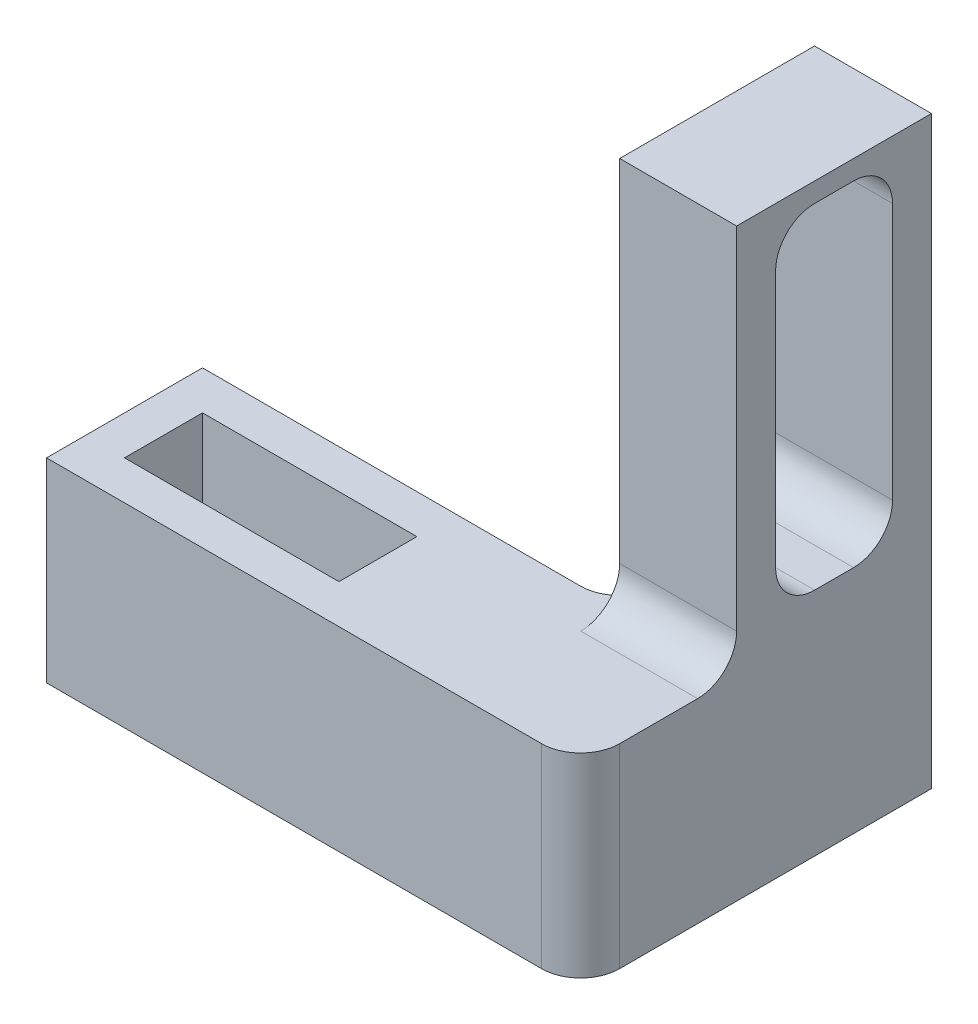
SolidWorks part; units mm, degrees
ref_plane "Front Plane" through (0, 0, 0) normal (0, 0, 1) x (1, 0, 0)
ref_plane "Top Plane" through (0, 0, 0) normal (0, 1, 0) x (1, 0, 0)
ref_plane "Right Plane" through (0, 0, 0) normal (1, 0, 0) x (0, 0, -1)
sketch "Sketch1" plane through (0, 0, 0) normal (0, 1, 0) x (1, 0, 0)
  line L1 (-2.5135, 3.907) -> (2.9865, 3.907)
  line L2 (-2.5135, 3.907) -> (-2.5135, 1.907)
  line L3 (-2.5135, 1.907) -> (2.9865, 1.907)
  line L4 (2.9865, 3.907) -> (2.9865, 1.907)
  line L5 (-3.5135, 4.907) -> (3.9865, 4.907)
  line L6 (-3.5135, 4.907) -> (-3.5135, 0.907)
  line L7 (-3.5135, 0.907) -> (3.9865, 0.907)
  line L8 (3.9865, 4.907) -> (3.9865, 0.907)
  dimension "D1" = 2
  dimension "D2" = 5.5
  dimension "D3" = 1
  dimension "D4" = 1
  dimension "D5" = 1
  dimension "D6" = 1
extrude "Boss-Extrude1" add sketch "Sketch1" along normal blind 5
sketch "Sketch2" plane through (0, 0, -4.907) normal (0, 0, -1) x (-1, 0, 0)
  line L1 (-3.9865, 5) -> (-10.1865, 5)
  line L2 (-3.9865, 5) -> (-3.9865, 0)
  line L3 (-3.9865, 0) -> (-10.1865, 0)
  line L4 (-10.1865, 5) -> (-10.1865, 0)
  circle A0 centre (-0.2365, 2.5) radius 6.5 construction
  dimension "D1" = 13
  dimension "D2" = 6.2
extrude "Boss-Extrude2" add sketch "Sketch2" against normal blind 4
sketch "Sketch3" plane through (0, 0, -4.907) normal (0, 0, -1) x (-1, 0, 0)
  line L0 (-10.1865, 0) -> (3.5135, 0) construction
  line L1 (-10.1865, 5) -> (-7.1865, 5)
  line L2 (-10.1865, 5) -> (-10.1865, 0)
  line L3 (-10.1865, 0) -> (-7.1865, 0)
  line L4 (-7.1865, 5) -> (-7.1865, 0)
  dimension "D1" = 3
extrude "Boss-Extrude3" add sketch "Sketch3" along normal blind 5
sketch "Sketch4" plane through (0, 5, 0) normal (0, 1, 0) x (1, 0, 0)
  line L0 (10.1865, 0.907) -> (10.1865, 9.907) construction
  line L1 (7.1865, 9.907) -> (10.1865, 9.907)
  line L2 (7.1865, 9.907) -> (7.1865, 4.9094)
  line L3 (7.1865, 4.9094) -> (10.1865, 4.9094)
  line L4 (10.1865, 9.907) -> (10.1865, 4.9094)
extrude "Boss-Extrude4" add sketch "Sketch4" along normal blind 10
sketch "Sketch5" plane through (10.1865, 0, 0) normal (1, 0, 0) x (0, 0, -1)
  line L0 (4.9094, 15) -> (4.9094, 5) construction
  line L1 (5.9094, 14.5) -> (8.9094, 14.5)
  line L2 (5.9094, 14.5) -> (5.9094, 5.9101)
  line L3 (5.9094, 5.9101) -> (8.9094, 5.9101)
  line L4 (8.9094, 14.5) -> (8.9094, 5.9101)
  line L5 (4.9094, 15) -> (9.907, 15) construction
  dimension "D1" = 1
  dimension "D2" = 3
  dimension "D3" = 0.5
extrude "Cut-Extrude1" cut sketch "Sketch5" against normal blind 10
fillet "Fillet1" radius 1 1 edges
fillet "Fillet2" radius 1 1 edges at (10.1865, 2.5, -0.907)
fillet "Fillet3" radius 1 1 edges
sketch "Sketch6" plane through (0, 15, 0) normal (0, 1, 0) x (1, 0, 0)
  line L1 (7.1865, 5.907) -> (-3.5135, 5.907)
  line L2 (7.1865, 5.907) -> (7.1865, 3.9094)
  line L3 (7.1865, 3.9094) -> (-3.5135, 3.9094)
  line L4 (-3.5135, 5.907) -> (-3.5135, 3.9094)
extrude "Cut-Extrude2" cut sketch "Sketch6" against normal blind 10
fillet "Fillet4" radius 1 1 edges at (8.6865, 5.9101, -8.9094)
fillet "Fillet5" radius 1 1 edges at (8.6865, 5.9101, -5.9094)
fillet "Fillet6" radius 1 1 edges at (8.6865, 14.5, -5.9094)
fillet "Fillet7" radius 1 1 edges at (8.6865, 14.5, -8.9094)
